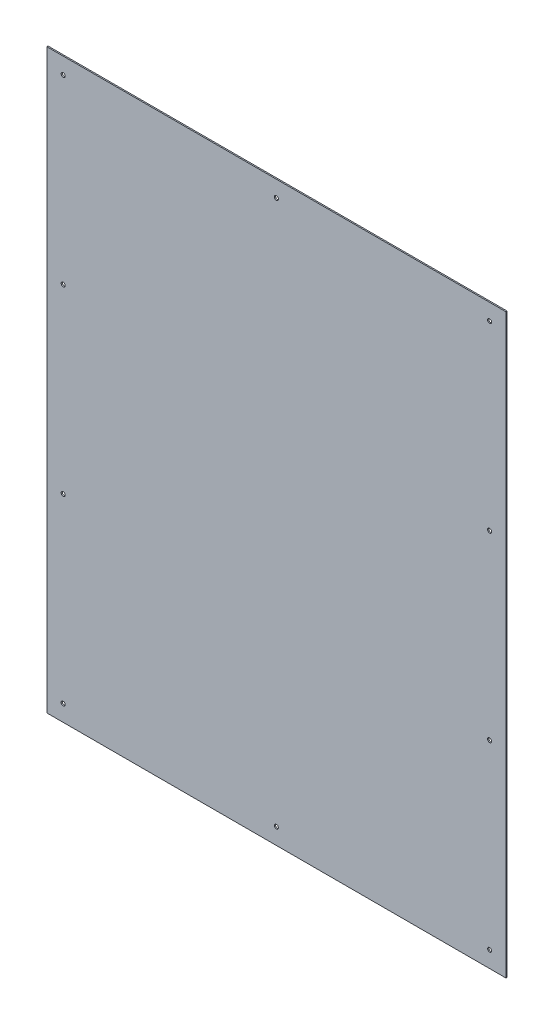
SolidWorks part; units mm, degrees
ref_plane "Alzado" through (0, 0, 0) normal (0, 0, 1) x (1, 0, 0)
ref_plane "Planta" through (0, 0, 0) normal (0, 1, 0) x (1, 0, 0)
ref_plane "Vista lateral" through (0, 0, 0) normal (1, 0, 0) x (0, 0, -1)
sketch "Croquis1" plane through (0, 0, 0) normal (0, 0, 1) x (1, 0, 0)
  line L1 (-358, 450) -> (358, 450)
  line L2 (-358, 450) -> (-358, -450)
  line L3 (-358, -450) -> (358, -450)
  line L4 (358, 450) -> (358, -450)
  line L5 (-358, 450) -> (358, -450) construction
  line L6 (-358, -450) -> (358, 450) construction
  point P0 (0, 0)
  dimension "D1" = 716
  dimension "D2" = 900
extrude "Saliente-Extruir1" add sketch "Croquis1" along normal blind 1.9
sketch "Croquis2" plane through (0, 0, 1.9) normal (0, 0, 1) x (1, 0, 0)
  line L0 (358, 450) -> (-358, 450) construction
  line L1 (-332.6, -424.6) -> (332.6, -424.6) construction
  line L2 (-332.6, -424.6) -> (-332.6, 424.6) construction
  line L3 (-332.6, 424.6) -> (332.6, 424.6) construction
  line L4 (332.6, -424.6) -> (332.6, 424.6) construction
  line L5 (-332.6, -424.6) -> (332.6, 424.6) construction
  line L6 (-332.6, 424.6) -> (332.6, -424.6) construction
  line L7 (-358, 450) -> (-358, -450) construction
  line L8 (0, 0) -> (0, 424.6) construction
  line L9 (0, 0) -> (251.9719, 0) construction
  circle A0 centre (-332.6, 424.6) radius 3.175
  circle A1 centre (332.6, 424.6) radius 3.175
  circle A2 centre (0, 424.6) radius 3.175
  circle A3 centre (332.6, -424.6) radius 3.175
  circle A4 centre (0, -424.6) radius 3.175
  circle A5 centre (-332.6, -424.6) radius 3.175
  circle A6 centre (-332.6, 141.54) radius 3.175
  circle A7 centre (-332.6, -141.52) radius 3.175
  circle A8 centre (332.6, -141.52) radius 3.175
  circle A9 centre (332.6, 141.54) radius 3.175
  point P0 (0, 0)
  dimension "D3" = 6.35
  dimension "D4" = 6.35
  dimension "D5" = 6.35
  dimension "D1" = 25.4
  dimension "D2" = 25.4
  dimension "D6" = 3
extrude "Cortar-Extruir1" cut sketch "Croquis2" against normal blind 10
